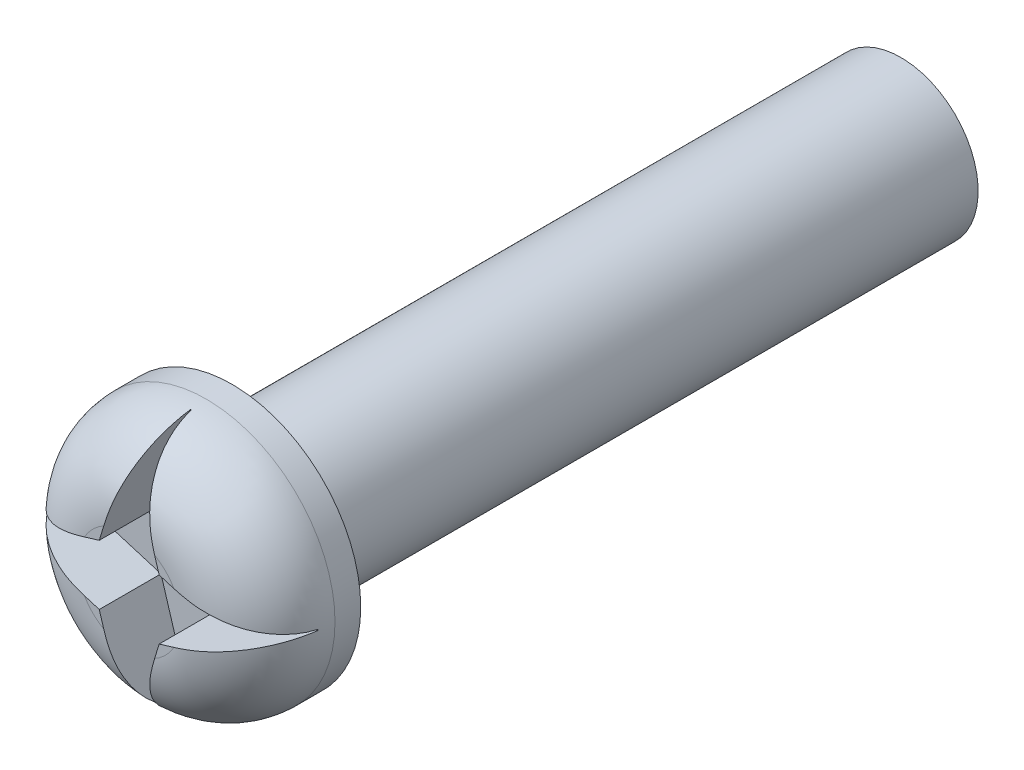
SolidWorks part; units mm, degrees
ref_plane "Front Plane" through (0, 0, 0) normal (0, 0, 1) x (1, 0, 0)
ref_plane "Top Plane" through (0, 0, 0) normal (0, 1, 0) x (1, 0, 0)
ref_plane "Right Plane" through (0, 0, 0) normal (1, 0, 0) x (0, 0, -1)
sketch "Sketch1" plane through (0, 0, 0) normal (0, 0, 1) x (1, 0, 0)
  circle A0 centre (0, 0) radius 1.5
extrude "Boss-Extrude1" add sketch "Sketch1" along normal blind 13
sketch "Sketch2" plane through (0, 0, 13) normal (0, 0, 1) x (1, 0, 0)
  circle A0 centre (0, 0) radius 2.5
extrude "Boss-Extrude2" add sketch "Sketch2" along normal blind 2
fillet "Fillet1" radius 1.5 1 edges at (2.5, 0, 15)
sketch "Sketch3" plane through (0, 0, 15) normal (0, 0, 1) x (1, 0, 0)
  line L0 (2.5, 0) -> (0.5818, 0.5818)
  line L1 (0, 2.5) -> (0.5818, 0.5818)
  line L2 (0, 2.5) -> (-0.5818, 0.5818)
  line L3 (2.5, 0) -> (0.5818, -0.5818)
  line L4 (0, -2.5) -> (0.5818, -0.5818)
  line L5 (0, -2.5) -> (-0.5818, -0.5818)
  line L6 (-2.5, 0) -> (-0.5818, -0.5818)
  line L7 (-2.5, 0) -> (-0.5818, 0.5818)
  circle A1 centre (0, 0) radius 2.5 construction
  point P19 (0, 0)
  dimension "D1" = 4
extrude "Cut-Extrude1" cut sketch "Sketch3" against normal blind 1.2
